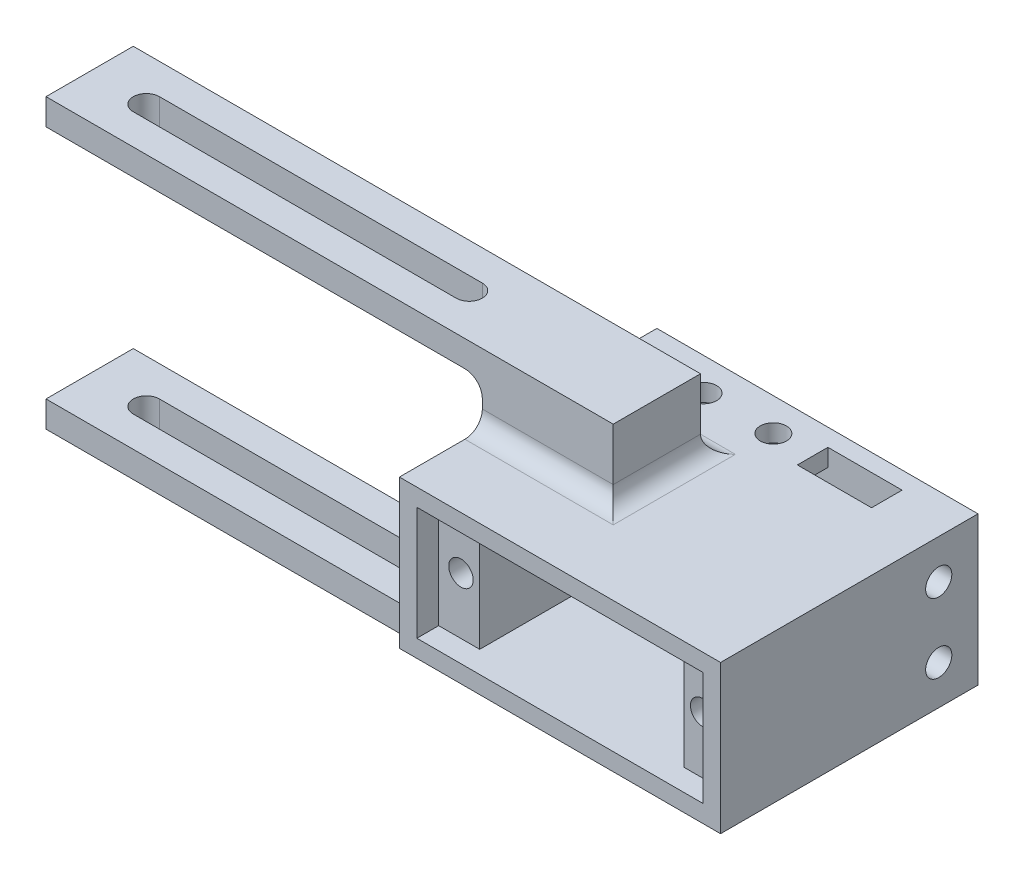
SolidWorks part; units mm, degrees
ref_plane "Front Plane" through (0, 0, 0) normal (0, 0, 1) x (1, 0, 0)
ref_plane "Top Plane" through (0, 0, 0) normal (0, 1, 0) x (1, 0, 0)
ref_plane "Right Plane" through (0, 0, 0) normal (1, 0, 0) x (0, 0, -1)
sketch "Sketch1" plane through (0, 0, 0) normal (0, 0, 1) x (1, 0, 0)
  line L0 (-13.85, 0) -> (13.85, 0)
  line L1 (-16.4, 6.5) -> (16.4, 6.5)
  line L2 (-16.4, 6.5) -> (-16.4, -6.5)
  line L3 (-16.4, -6.5) -> (16.4, -6.5)
  line L4 (16.4, 6.5) -> (16.4, -6.5)
  line L5 (-16.4, 6.5) -> (16.4, -6.5) construction
  line L6 (-16.4, -6.5) -> (16.4, 6.5) construction
  line L7 (-18.4, 8.5) -> (-18.4, -8.5)
  line L8 (-18.4, -8.5) -> (18.4, -8.5)
  line L13 (18.4, 8.5) -> (18.4, -8.5)
  line L14 (-18.4, 8.5) -> (18.4, 8.5)
  line L16 (-11.7, 6.5) -> (11.7, 6.5)
  line L17 (-11.7, 6.5) -> (-11.7, -6.5)
  line L18 (-11.7, -6.5) -> (11.7, -6.5)
  line L19 (11.7, 6.5) -> (11.7, -6.5)
  line L20 (-11.7, 6.5) -> (11.7, -6.5) construction
  line L21 (-11.7, -6.5) -> (11.7, 6.5) construction
  circle A0 centre (-13.85, 0) radius 1.4
  circle A1 centre (13.85, 0) radius 1.4
  point P0 (0, 0)
  point P7 (0, 0)
  dimension "D2" = 2.8
  dimension "D7" = 2.8
  dimension "D1" = 32.8
  dimension "D3" = 27.7
  dimension "D4" = 13
  dimension "D5" = 2
  dimension "D6" = 23.4
extrude "Boss-Extrude1" add sketch "Sketch1" along normal blind 2
sketch "Sketch4" plane through (0, 0, 2) normal (0, 0, 1) x (1, 0, 0)
  line L0 (-13.85, 0) -> (13.85, 0) construction
  line L1 (-13.85, 0) -> (13.85, 0)
  line L4 (-18.4, 8.5) -> (-18.4, -8.5)
  line L5 (-18.4, -8.5) -> (18.4, -8.5)
  line L6 (18.4, -8.5) -> (18.4, 8.5)
  line L7 (18.4, 8.5) -> (-18.4, 8.5)
  line L8 (-18.4, 8.5) -> (-18.4, -8.5)
  line L9 (-18.4, -8.5) -> (18.4, -8.5)
  line L10 (18.4, -8.5) -> (18.4, 8.5)
  line L11 (18.4, 8.5) -> (-18.4, 8.5)
  line L12 (16.4, 6.5) -> (-16.4, 6.5)
  line L13 (16.4, -6.5) -> (16.4, 6.5)
  line L14 (-16.4, -6.5) -> (16.4, -6.5)
  line L15 (-16.4, 6.5) -> (-16.4, -6.5)
  line L16 (16.4, 6.5) -> (-16.4, 6.5)
  line L17 (16.4, -6.5) -> (16.4, 6.5)
  line L18 (-16.4, -6.5) -> (16.4, -6.5)
  line L19 (-16.4, 6.5) -> (-16.4, -6.5)
  line L20 (11.7, 6.5) -> (-11.7, 6.5)
  line L21 (-11.7, 6.5) -> (-11.7, -6.5)
  line L22 (-11.7, -6.5) -> (11.7, -6.5)
  line L23 (11.7, -6.5) -> (11.7, 6.5)
  line L24 (11.7, 6.5) -> (-11.7, 6.5)
  line L25 (-11.7, 6.5) -> (-11.7, -6.5)
  line L26 (-11.7, -6.5) -> (11.7, -6.5)
  line L27 (11.7, -6.5) -> (11.7, 6.5)
  circle A1 centre (13.85, 0) radius 1.4
  circle A2 centre (13.85, 0) radius 1.4
  circle A3 centre (-13.85, 0) radius 1.4
  circle A4 centre (-13.85, 0) radius 1.4
  line M15 (-16.4, -6.5) -> (-11.7, -6.5)
  line M17 (-11.7, 6.5) -> (-16.4, 6.5)
  line M18 (-16.4, 6.5) -> (-16.4, -6.5)
  dimension "D1" = 0
  dimension "D2" = 0
  dimension "D3" = 0
  dimension "D4" = 0
  dimension "D5" = 0
extrude "Boss-Extrude3" add sketch "Sketch4" along normal blind 2.5 and the other way blind 25 contours L10 L11 L8 L9 L18 L16 L17 M15 M18 M17 | L24 L25 L26 L27
sketch "Sketch5" plane through (0, 0, 0) normal (0, 0, -1) x (-1, 0, 0)
  line L0 (-11.7, 6.5) -> (-16.4, 6.5) construction
  line L1 (-16.4, 6.5) -> (-16.4, -6.5) construction
  line L2 (-16.4, -6.5) -> (-11.7, -6.5) construction
  line L3 (-11.7, -6.5) -> (-11.7, 6.5) construction
  line L4 (11.7, -6.5) -> (16.4, -6.5) construction
  line L5 (16.4, -6.5) -> (16.4, 6.5) construction
  line L6 (16.4, 6.5) -> (11.7, 6.5) construction
  line L7 (11.7, 6.5) -> (11.7, -6.5) construction
  line L8 (-11.7, 6.5) -> (-16.4, 6.5)
  line L9 (-16.4, 6.5) -> (-16.4, -6.5)
  line L10 (-16.4, -6.5) -> (-11.7, -6.5)
  line L11 (-11.7, -6.5) -> (-11.7, 6.5)
  line L12 (11.7, -6.5) -> (16.4, -6.5)
  line L13 (16.4, -6.5) -> (16.4, 6.5)
  line L14 (16.4, 6.5) -> (11.7, 6.5)
  line L15 (11.7, 6.5) -> (11.7, -6.5)
  circle A0 centre (13.85, 0) radius 1.4 construction
  circle A1 centre (-13.85, 0) radius 1.4 construction
  circle A2 centre (13.85, 0) radius 1.4
  circle A3 centre (-13.85, 0) radius 1.4
extrude "Boss-Extrude4" add sketch "Sketch5" along normal up to surface (23 mm away) up to face at (0, 0, -23)
sketch "Sketch6" plane through (0, 0, -23) normal (0, 0, -1) x (-1, 0, 0)
  line L4 (-18.4, 8.5) -> (-18.4, -8.5)
  line L5 (-18.4, -8.5) -> (18.4, -8.5)
  line L6 (18.4, -8.5) -> (18.4, 8.5)
  line L7 (18.4, 8.5) -> (-18.4, 8.5)
  line L8 (-18.4, 8.5) -> (-18.4, -8.5)
  line L9 (-18.4, -8.5) -> (18.4, -8.5)
  line L10 (18.4, -8.5) -> (18.4, 8.5)
  line L11 (18.4, 8.5) -> (-18.4, 8.5)
  dimension "D1" = 0
extrude "Boss-Extrude5" add sketch "Sketch6" along normal blind 2
sketch "Sketch7" plane through (0, 8.5, 0) normal (0, 1, 0) x (1, 0, 0)
  line L0 (11.7, -2) -> (11.7, 23) construction
  line L1 (11.7, 19.5) -> (3.2, 19.5)
  line L2 (11.7, 19.5) -> (11.7, 23)
  line L3 (11.7, 23) -> (3.2, 23)
  line L4 (3.2, 19.5) -> (3.2, 23)
  line L5 (11.7, 19.5) -> (3.2, 23) construction
  line L6 (11.7, 23) -> (3.2, 19.5) construction
  line L7 (11.7, 23) -> (-11.7, 23) construction
  line L8 (-18.4, 25) -> (18.4, 25) construction
  circle A0 centre (-1.3001, 21.25) radius 1.5
  circle A1 centre (-9.3001, 21.25) radius 1.5
  point P0 (7.45, 21.25)
  dimension "D3" = 3
  dimension "D4" = 3.0001
  dimension "D5" = 3.75
  dimension "D1" = 8.5
  dimension "D2" = 3.5
  dimension "D6" = 2
extrude "Cut-Extrude1" cut sketch "Sketch7" against normal through all
sketch "Sketch8" plane through (18.4, 0, 0) normal (1, 0, 0) x (0, 0, -1)
  line L0 (25, 0) -> (15.6118, 0) construction
  line L2 (25, 8.5) -> (25, -8.5) construction
  line L4 (25, 8.5) -> (-4.5, 8.5) construction
  circle A0 centre (20.5, 4) radius 1.5
  circle A1 centre (20.5, -4) radius 1.5
  dimension "D1" = 3
  dimension "D2" = 3
  dimension "D3" = 3
extrude "Cut-Extrude2" cut sketch "Sketch8" against normal through all
sketch "Sketch9" plane through (0, 0, -25) normal (0, 0, -1) x (-1, 0, 0)
  line L0 (8.9, 0) -> (-8.9, 0) construction
  line L1 (8.9, -1.5) -> (-8.9, -1.5)
  line L2 (8.9, 1.5) -> (-8.9, 1.5)
  line L3 (-18.4, 8.5) -> (-18.4, -8.5) construction
  arc A0 (8.9, -1.5) -> (8.9, 1.5) centre (8.9, 0) ccw
  arc A1 (-8.9, 1.5) -> (-8.9, -1.5) centre (-8.9, 0) ccw
  point P2 (0, 0)
  dimension "D1" = 1.5
  dimension "D2" = 8
extrude "Cut-Extrude3" cut sketch "Sketch9" against normal through all
ref_plane "Plane1" through (0, 0, -15) normal (0, 0, -1) x (-1, 0, 0)
sketch "Sketch10" plane through (0, 0, -15) normal (0, 0, -1) x (-1, 0, 0)
  line L0 (18.4, -8.5) -> (18.4, 8.5) construction
  line L13 (18.4, -13.5) -> (68.4, -13.5)
  line L14 (18.4, -13.5) -> (18.4, -16.5)
  line L15 (18.4, -16.5) -> (68.4, -16.5)
  line L16 (68.4, -13.5) -> (68.4, -16.5)
  line L17 (10.4, 0) -> (48.7114, 0) construction
  line L18 (18.4, 16.5) -> (68.4, 16.5)
  line L19 (68.4, 13.5) -> (68.4, 16.5)
  line L20 (18.4, 13.5) -> (68.4, 13.5)
  line L21 (18.4, 13.5) -> (18.4, 16.5)
  line L22 (18.4, 8.5) -> (-18.4, 8.5) construction
  line L23 (18.4, 16.5) -> (3.4, 16.5)
  line L24 (18.4, 16.5) -> (18.4, -16.5)
  line L25 (18.4, -16.5) -> (3.4, -16.5)
  line L26 (3.4, 16.5) -> (3.4, -16.5)
  line L27 (3.4, 8.5) -> (18.4, 8.5)
  line L28 (3.4, 8.5) -> (3.4, -8.5)
  line L29 (3.4, -8.5) -> (18.4, -8.5)
  line L30 (18.4, 8.5) -> (18.4, -8.5)
  line L31 (-18.4, -8.5) -> (18.4, -8.5) construction
  arc A0 (8.9, -1.5) -> (8.9, 1.5) centre (8.9, 0) ccw construction
  dimension "D2" = 50
  dimension "D3" = 30
  dimension "D1" = 3
  dimension "D4" = 15
extrude "Boss-Extrude6" add sketch "Sketch10" against normal blind 10 contours L29 L26 L25 L14 L24 | L26 L27 L24 L21 L23 | L21 L20 L19 L18
sketch "Sketch12" plane through (0, -13.5, 0) normal (0, 1, 0) x (1, 0, 0)
  line L0 (-24.9, 10) -> (-61.9, 10) construction
  line L1 (-24.9, 8.5) -> (-61.9, 8.5)
  line L2 (-24.9, 11.5) -> (-61.9, 11.5)
  line L3 (-68.4, 5) -> (-68.4, 15) construction
  line L5 (-18.4, 5) -> (-18.4, 15) construction
  arc A0 (-24.9, 8.5) -> (-24.9, 11.5) centre (-24.9, 10) ccw
  arc A1 (-61.9, 11.5) -> (-61.9, 8.5) centre (-61.9, 10) ccw
  point P2 (-43.4, 10)
  point P9 (-68.4, 10)
  dimension "D1" = 1.5
  dimension "D2" = 5
  dimension "D3" = 5
extrude "Cut-Extrude4" cut sketch "Sketch12" against normal through all and the other way through all
fillet "Fillet1" radius 2 8 edges at (-18.4, -13.5, -10) (-18.4, 13.5, -10) (-10.9, 8.5, -15) (-10.9, 8.5, -5) (-3.4, 8.5, -10) (-10.9, -8.5, -5) (-3.4, -8.5, -10) (-10.9, -8.5, -15)
